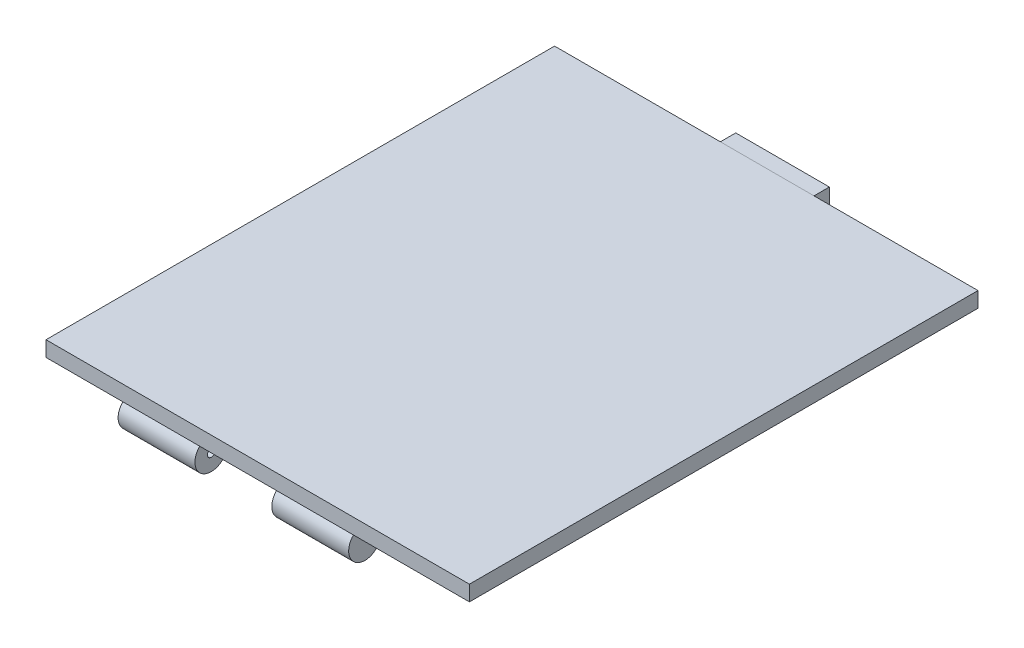
SolidWorks part; units mm, degrees
ref_plane "Front Plane" through (0, 0, 0) normal (0, 0, 1) x (1, 0, 0)
ref_plane "Top Plane" through (0, 0, 0) normal (0, 1, 0) x (1, 0, 0)
ref_plane "Right Plane" through (0, 0, 0) normal (1, 0, 0) x (0, 0, -1)
sketch "Sketch1" plane through (0, 0, 0) normal (0, 1, 0) x (1, 0, 0)
  line L0 (0, 0) -> (0, -66.17)
  line L1 (0, 0) -> (55.09, 0)
  line L2 (0, -66.17) -> (55.09, -66.17)
  line L3 (55.09, 0) -> (55.09, -66.17)
  dimension "D1" = 66.17
  dimension "D2" = 55.09
extrude "Boss-Extrude1" add sketch "Sketch1" along normal blind 2
ref_plane "Plane1" through (10, 0, 0) normal (-1, 0, 0) x (0, 0, 1)
sketch "Sketch2" plane through (10, 0, 0) normal (-1, 0, 0) x (0, 0, 1)
  line L0 (66.17, 0) -> (64.67, 0)
  line L1 (30.2995, 0) -> (-30.2995, 0) construction
  line L2 (64.67, 0) -> (64.67, -1.5)
  circle A0 centre (64.67, -1.5) radius 0.5
  circle A1 centre (64.67, -1.5) radius 2.1213
  dimension "D3" = 1
  dimension "D1" = 1.5
  dimension "D2" = 1.5
extrude "Boss-Extrude2" add sketch "Sketch2" against normal blind 10
ref_plane "Plane2" through (30, 0, 0) normal (-1, 0, 0) x (0, 0, 1)
sketch "Sketch3" plane through (30, 0, 0) normal (-1, 0, 0) x (0, 0, 1)
  circle A0 centre (64.67, -1.5) radius 0.5141
  circle A1 centre (64.67, -1.5) radius 2.1213
extrude "Boss-Extrude3" add sketch "Sketch3" against normal blind 10 contours A1
sketch "Sketch4" plane through (0, 0, 0) normal (0, 0, -1) x (-1, 0, 0)
  line L0 (-55.09, 0) -> (-33.7549, 0)
  line L1 (-55.09, 0) -> (0, 0) construction
  line L2 (-27.545, 0) -> (-32.5666, 0)
  line L3 (-32.5666, 0) -> (-32.5666, -4.5)
  line L4 (-32.5666, -4.5) -> (-22.5917, -4.5)
  line L5 (-22.5917, -4.5) -> (-22.5917, 0)
  line L6 (30.2995, 0) -> (-30.2995, 0) construction
  line L7 (-22.5917, 0) -> (-32.5666, 0)
  line L8 (-32.5666, -4.5) -> (-32.5666, -5.4933)
  line L9 (-32.5666, -5.4933) -> (-22.5917, -5.4933)
  line L10 (-22.5917, -5.4933) -> (-22.5917, -4.7521)
  line L12 (-21.5702, 0) -> (-21.5702, -6.5177)
  line L13 (-21.5702, -6.5177) -> (-33.7549, -6.5177)
  line L14 (-33.7549, -6.5177) -> (-33.7549, 0)
  line L15 (-32.5666, 0) -> (-22.5917, 0)
  line L16 (-32.5666, -4.5) -> (-22.5917, -4.5)
  line L17 (-22.5917, -4.7521) -> (-22.5917, -4.5)
  line L18 (-22.5917, -4.7521) -> (-22.5917, -4.5)
  line L19 (-33.7549, 0) -> (-33.7549, 2)
  line L20 (-55.09, 2) -> (0, 2) construction
  line L21 (-33.7549, 2) -> (-21.5702, 2)
  line L22 (-21.5702, 2) -> (-21.5702, 0)
  line L23 (-32.5666, 0) -> (-27.545, 0)
  line M5 (-55.09, 0) -> (0, 0)
  line M7 (0, 2) -> (-55.09, 2)
  dimension "D1" = 4.5
extrude "Boss-Extrude4" add sketch "Sketch4" along normal blind 2 separate body contours L17 L10 L9 L8 L3 L0 L14 L13 L12 L5 M5 | L4 L5 L0 L3 M5 | L22 L19 M7 M5
sketch "Sketch6" plane through (21.5702, 0, 0) normal (-1, 0, 0) x (0, 0, 1)
  line L0 (-2, -6.5177) -> (0, -5.7752)
  line L1 (0, 2) -> (0, -6.5177) construction
  line L2 (0, -5.7752) -> (0, -6.5177)
  line L3 (0, -6.5177) -> (-2, -6.5177)
extrude "Cut-Extrude1" cut sketch "Sketch6" against normal through all both and the other way through all
